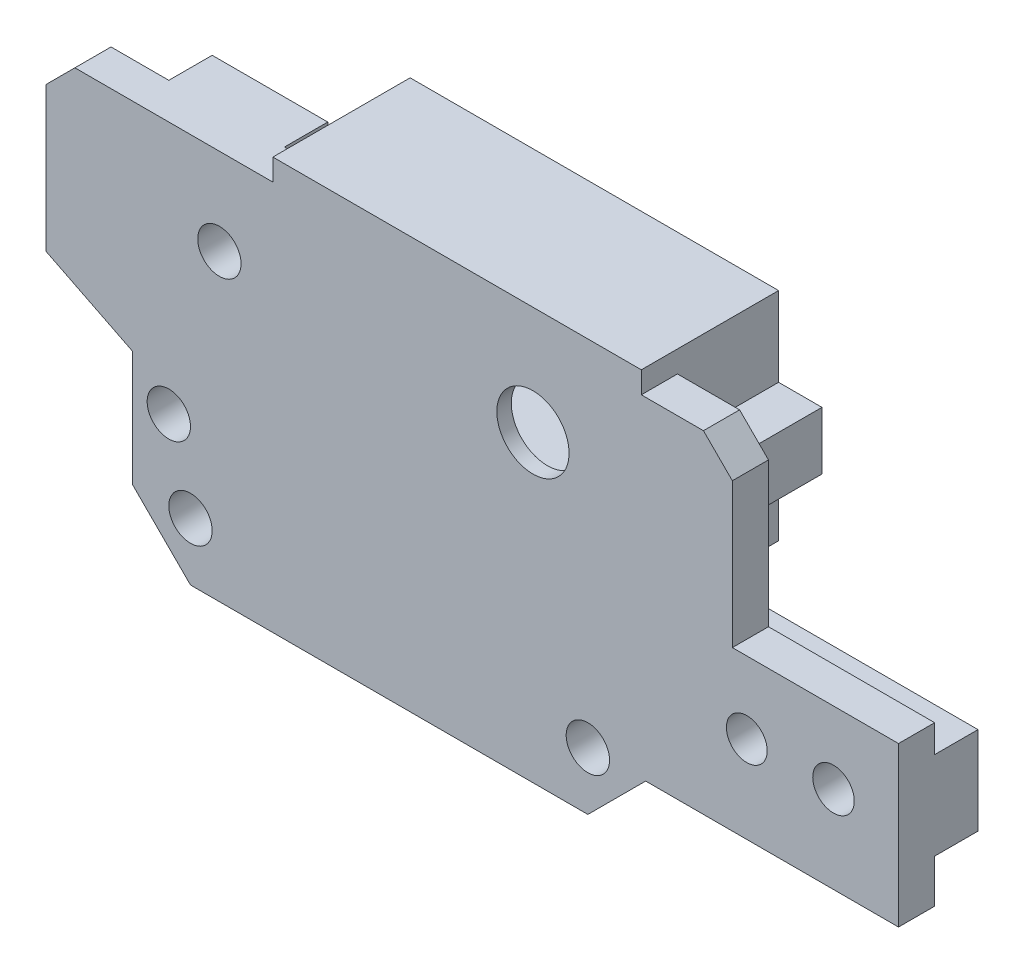
SolidWorks part; units mm, degrees
ref_plane "前视基准面" through (0, 0, 0) normal (0, 0, 1) x (1, 0, 0)
ref_plane "上视基准面" through (0, 0, 0) normal (0, 1, 0) x (1, 0, 0)
ref_plane "右视基准面" through (0, 0, 0) normal (1, 0, 0) x (0, 0, -1)
other "Configuration Table"
sketch "草图1" plane through (0, 0, 0) normal (0, 0, 1) x (1, 0, 0)
  line L0 (4, 0) -> (0, 4)
  line L1 (4, 0) -> (31.5, 0)
  line L2 (0, 4) -> (0, 12)
  line L4 (35.5, 4) -> (35.5, 12)
  line L5 (31.5, 0) -> (35.5, 4)
  line L6 (-10, 27) -> (45.5, 27)
  line L7 (17.75, 12) -> (17.75, 35.6518) construction
  line L8 (-10, 27) -> (-10, 17)
  line L9 (-10, 17) -> (0, 12)
  line L10 (45.5, 17) -> (35.5, 12)
  line L11 (45.5, 27) -> (45.5, 17)
  circle A0 centre (4, 4) radius 1.5
  circle A1 centre (31.5, 4) radius 1.5
  circle A2 centre (7, 21) radius 1.5
  circle A3 centre (28.5, 21) radius 1.5
  point P0 (0, 0)
  point P3 (35.5, 0)
  dimension "D3" = 4
  dimension "D7" = 3
  dimension "D8" = 3
  dimension "D9" = 3
  dimension "D15" = 3
  dimension "D16" = 3
  dimension "D1" = 35.5
  dimension "D2" = 12
  dimension "D4" = 4
  dimension "D5" = 4
  dimension "D6" = 4
  dimension "D10" = 3
  dimension "D13" = 17
  dimension "D14" = 17
  dimension "D17" = 27
  dimension "D18" = 10
  dimension "D19" = 5
extrude "凸台-拉伸1" add sketch "草图1" along normal blind 2.5
sketch "草图2" plane through (0, 0, 0) normal (0, 0, -1) x (-1, 0, 0)
  line L0 (-35.2, 28.5) -> (-9.7, 28.5)
  line L1 (-33.7, 15) -> (-11.2, 15)
  line L2 (-33.7, 15) -> (-33.7, 27)
  line L3 (-33.7, 27) -> (-11.2, 27)
  line L4 (-11.2, 15) -> (-11.2, 27)
  line L5 (-9.7, 13.5) -> (-9.7, 19)
  line L6 (-35.2, 13.5) -> (-9.7, 13.5)
  line L7 (-35.2, 13.5) -> (-35.2, 19)
  line L8 (-22.45, 28.5) -> (-22.45, 38.9832) construction
  line L9 (-35.2, 19) -> (-38.2, 19)
  line L11 (-35.2, 23) -> (-38.2, 23)
  line L12 (-38.2, 19) -> (-38.2, 23)
  line L13 (-9.7, 19) -> (-8.2, 19)
  line L15 (-9.7, 23) -> (-8.2, 23)
  line L16 (-35.2, 23) -> (-35.2, 28.5)
  line L17 (-35.2, 13.5) -> (-35.2, 28.5) construction
  line L18 (-9.7, 23) -> (-9.7, 28.5)
  line L19 (-9.7, 13.5) -> (-9.7, 28.5) construction
  line L20 (-8.2, 23) -> (-8.2, 22.241)
  line L21 (-8.2, 19.759) -> (-8.2, 19)
  circle A0 centre (-28.5, 21) radius 1.5 construction
  circle A1 centre (-35.95, 21) radius 1.45
  arc A2 (-8.2, 22.241) -> (-8.2, 19.759) centre (-8.95, 21) ccw
  dimension "D9" = 2.9
  dimension "D10" = 2.9
  dimension "D11" = 27
  dimension "D13" = 2
  dimension "D16" = 21
  dimension "D1" = 22.5
  dimension "D2" = 12
  dimension "D3" = 5.2
  dimension "D4" = 6
  dimension "D6" = 3
  dimension "D7" = 4
  dimension "D8" = 4
  dimension "D12" = 13.5
  dimension "D14" = 2.25
  dimension "D15" = 1.5
  dimension "D17" = 0.759
  dimension "D5" = 1.5
extrude "凸台-拉伸2" add sketch "草图2" along normal blind 7 and the other way blind 2.5
sketch "草图3" plane through (0, 0, 0) normal (0, 0, -1) x (-1, 0, 0)
  line L0 (0, 12) -> (0, 4) construction
  line L1 (0, 7) -> (-8, 7)
  line L2 (0, 7) -> (0, 27)
  line L3 (0, 27) -> (-8, 27)
  line L4 (-8, 7) -> (-8, 27)
  line L5 (-9.7, 27) -> (10, 27) construction
  circle A0 centre (-2.5, 9.5) radius 1.5
  circle A1 centre (-2.5, 18.5) radius 1.5
  dimension "D3" = 9
  dimension "D5" = 3
  dimension "D6" = 3
  dimension "D1" = 20
  dimension "D2" = 8
  dimension "D4" = 2.5
  dimension "D7" = 2.5
  dimension "D8" = 2.5
extrude "凸台-拉伸3" add sketch "草图3" along normal blind 3
sketch "草图4" plane through (0, 0, -3) normal (0, 0, -1) x (-1, 0, 0)
  circle A0 centre (-7, 21) radius 1.5 construction
  circle A3 centre (-2.5, 9.5) radius 1.5
  circle A4 centre (-2.5, 9.5) radius 1.5
  circle A5 centre (-7, 21) radius 1.5
  dimension "D2" = 0
extrude "切除-拉伸1" cut sketch "草图4" against normal through all
sketch "草图5" plane through (0, 0, 2.5) normal (0, 0, 1) x (1, 0, 0)
  circle A0 centre (2.5, 18.5) radius 2.75
  circle A1 centre (2.5, 9.5) radius 2.75
  dimension "D1" = 5.5
sketch "草图6" plane through (0, 0, 0) normal (0, 0, -1) x (-1, 0, 0)
  circle A0 centre (-27, 21) radius 3.4913
  circle A1 centre (-28.5, 21) radius 1.5 construction
extrude "凸台-拉伸4" add sketch "草图6" against normal blind 2.5
sketch "草图7" plane through (0, 0, 0) normal (0, 0, -1) x (-1, 0, 0)
  line L0 (-33.7, 27) -> (-33.7, 15) construction
  circle A0 centre (-27.7, 21) radius 6
  dimension "D2" = 12
  dimension "D1" = 6
  dimension "D3" = 34.7605
extrude "切除-拉伸3" cut sketch "草图7" against normal blind 1.5
sketch "草图8" plane through (0, 0, 0) normal (0, 0, -1) x (-1, 0, 0)
  arc A0 (-21.7188, 17.9622) -> (-21.5856, 23.7599) centre (-21.7, 20.8622) ccw
  circle A1 centre (-27.7, 21) radius 6 construction
  arc A2 (-22.7611, 24.407) -> (-21.5856, 23.7599) centre (-21.5264, 25.2587) ccw
  arc A3 (-21.7188, 17.9622) -> (-22.9228, 17.3698) centre (-21.7285, 16.4623) ccw
  arc A4 (-27.7, 15) -> (-27.7, 27) centre (-27.7, 21) ccw construction
  arc A5 (-22.9228, 17.3698) -> (-22.7611, 24.407) centre (-27.7, 21) ccw
  dimension "D1" = 6
  dimension "D2" = 5.8
  dimension "D3" = 3
  dimension "D4" = 3
extrude "切除-拉伸4" cut sketch "草图8" against normal blind 1.5
sketch "草图9" plane through (0, 0, 1.5) normal (0, 0, -1) x (-1, 0, 0)
  circle A0 centre (-27.7, 21) radius 2.5
  dimension "D1" = 5
extrude "切除-拉伸5" cut sketch "草图9" against normal blind 1.5
sketch "草图10" plane through (0, 0, 2.5) normal (0, 0, 1) x (1, 0, 0)
  line L0 (-6, 27) -> (-6, 15)
  line L1 (41.5, 27) -> (41.5, 15)
  line L16 (0, 12) -> (0, 4)
  line L18 (0, 4) -> (4, 0)
  line L19 (4, 0) -> (31.5, 0)
  line L20 (31.5, 0) -> (35.5, 4)
  line L21 (35.5, 4) -> (35.5, 12)
  line L22 (35.5, 12) -> (45.5, 17)
  line L23 (45.5, 17) -> (45.5, 27)
  line L24 (45.5, 27) -> (35.2, 27)
  line L25 (35.2, 27) -> (35.2, 28.5)
  line L26 (35.2, 28.5) -> (9.7, 28.5)
  line L27 (9.7, 28.5) -> (9.7, 27)
  line L28 (9.7, 27) -> (-10, 27)
  line L29 (-10, 27) -> (-10, 17)
  line L30 (-10, 17) -> (0, 12)
  line L37 (41.5, 15) -> (45.5, 17)
  line L38 (45.5, 17) -> (45.5, 27)
  line L39 (45.5, 27) -> (41.5, 27)
  line L43 (-6, 27) -> (-10, 27)
  line L44 (-10, 27) -> (-10, 17)
  line L45 (-10, 17) -> (-6, 15)
  dimension "D1" = 0
  dimension "D2" = 4
  dimension "D3" = 4
extrude "切除-拉伸6" cut sketch "草图10" against normal through all
chamfer "倒角1" distance 2 angle 45 2 edges at (41.5, 27, 1.25) (-6, 27, 1.25)
sketch "草图11" plane through (0, 0, 2.5) normal (0, 0, 1) x (1, 0, 0)
  circle A0 centre (7, 21) radius 1.5 construction
  arc A1 (6.5, 22.4142) -> (6.5, 19.5858) centre (7, 21) ccw
  circle A2 centre (6, 21) radius 1.5
  circle M23 centre (7, 21) radius 1.5
  dimension "D1" = 1
extrude "切除-拉伸8" cut sketch "草图11" against normal through all contours A2 M23
sketch "草图12" plane through (0, 0, 2.5) normal (0, 0, 1) x (1, 0, 0)
  arc A0 (6.5, 19.5858) -> (6.5, 22.4142) centre (7, 21) ccw
  arc A1 (6.5, 19.5858) -> (6.5, 22.4142) centre (6, 21) ccw
extrude "凸台-拉伸7" add sketch "草图12" against normal blind 3
sketch "草图18" plane through (8, 0, 0) normal (1, 0, 0) x (0, 0, -1)
  line L0 (0, 13.0857) -> (3, 13.0857)
  line L1 (0, 19.882) -> (0, 7) construction
  line L2 (3, 19.882) -> (3, 7) construction
  line L3 (3, 13.0857) -> (3, 7)
  line L4 (3, 7) -> (0, 7)
  line L5 (0, 7) -> (0, 13.0857)
extrude "凸台-拉伸9" add sketch "草图18" along normal blind 45
sketch "草图19" plane through (0, 0, -3) normal (0, 0, -1) x (-1, 0, 0)
  circle A0 centre (-42.5, 10.0171) radius 1.411
  circle A1 centre (-48.5, 10.0171) radius 1.4367
  circle A2 centre (-2.5, 9.5) radius 1.5 construction
  dimension "D1" = 40
  dimension "D2" = 6
extrude "切除-拉伸9" cut sketch "草图19" against normal blind 45
sketch "草图20" plane through (35.5, 0, 0) normal (1, 0, 0) x (0, 0, -1)
  line L0 (-2.5, 15) -> (-2.5, 12)
  line L1 (-2.5, 12) -> (-2.5, 4)
  line L5 (0, 4) -> (0, 7)
  line L6 (0, 7) -> (0, 12)
  line L7 (0, 12) -> (0, 15)
  line L8 (0, 15) -> (-2.5, 15)
  line L9 (-2.5, 4) -> (0, 4)
extrude "凸台-拉伸10" add sketch "草图20" along normal blind 17.5
sketch "草图21" plane through (0, 0, 0) normal (0, 0, -1) x (-1, 0, 0)
  circle A0 centre (-48.5, 10.0171) radius 1.4367
  circle A1 centre (-42.5, 10.0171) radius 1.411
extrude "切除-拉伸10" cut sketch "草图21" against normal blind 17.5
